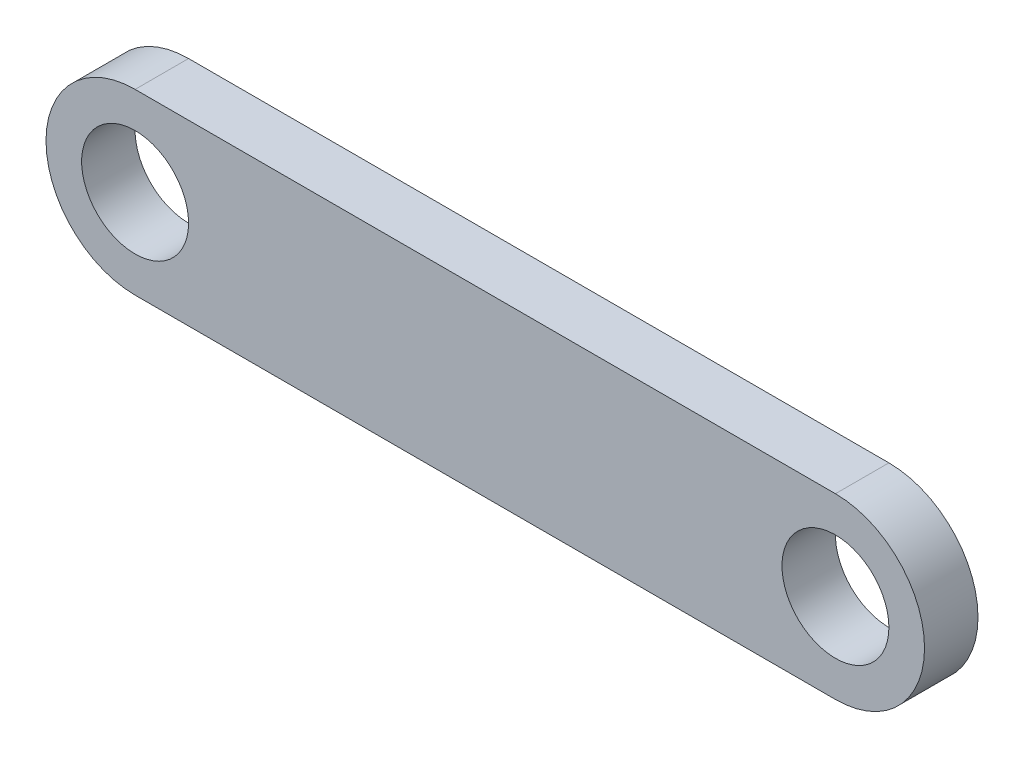
SolidWorks part; units mm, degrees
ref_plane "正面" through (0, 0, 0) normal (0, 0, 1) x (1, 0, 0)
ref_plane "平面" through (0, 0, 0) normal (0, 1, 0) x (1, 0, 0)
ref_plane "右側面" through (0, 0, 0) normal (1, 0, 0) x (0, 0, -1)
sketch "ｽｹｯﾁ1" plane through (0, 0, 0) normal (0, 0, 1) x (1, 0, 0)
  line L0 (-19.65, 0) -> (19.65, 0) construction
  line L1 (-19.65, 5) -> (19.65, 5)
  line L2 (-19.65, -5) -> (19.65, -5)
  arc A0 (-19.65, 5) -> (-19.65, -5) centre (-19.65, 0) ccw
  arc A1 (19.65, -5) -> (19.65, 5) centre (19.65, 0) ccw
  circle A2 centre (-19.65, 0) radius 3
  circle A3 centre (19.65, 0) radius 3
  point P2 (0, 0)
  dimension "D1" = 6
  dimension "D2" = 5
  dimension "D3" = 39.3
extrude "ﾎﾞｽ - 押し出し1" add sketch "ｽｹｯﾁ1" along normal blind 3
